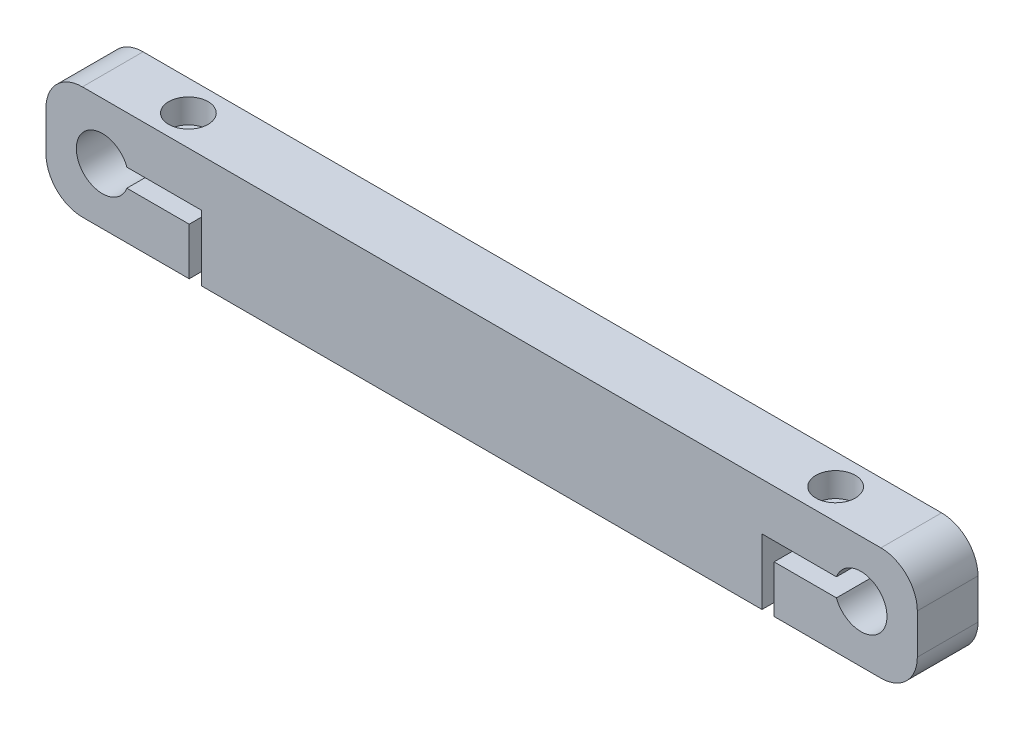
SolidWorks part; units mm, degrees
ref_plane "Alzado" through (0, 0, 0) normal (0, 0, 1) x (1, 0, 0)
ref_plane "Planta" through (0, 0, 0) normal (0, 1, 0) x (1, 0, 0)
ref_plane "Vista lateral" through (0, 0, 0) normal (1, 0, 0) x (0, 0, -1)
sketch "Croquis1" plane through (0, 0, 0) normal (0, 0, 1) x (1, 0, 0)
  line L0 (-62.5, 0) -> (62.5, 0) construction
  line L1 (-65.8, 9.3) -> (65.8, 9.3)
  line L2 (-71.8, 3.3) -> (-71.8, -3.3)
  line L3 (-65.8, -9.3) -> (65.8, -9.3)
  line L4 (71.8, 3.3) -> (71.8, -3.3)
  line L5 (-71.8, 9.3) -> (71.8, -9.3) construction
  line L6 (-71.8, -9.3) -> (71.8, 9.3) construction
  line L7 (-59.5641, 1.5) -> (-46.2, 1.5)
  line L8 (-46.2, 1.5) -> (-46.2, -9.3)
  line L9 (48.2, -1.5) -> (48.2, -9.3)
  line L10 (0, 9.3) -> (0, -9.3) construction
  line L11 (-60.6533, -1.5) -> (-48.2, -1.5)
  line L12 (-48.2, -1.5) -> (-48.2, -9.3)
  line L13 (46.2, 1.5) -> (46.2, -9.3)
  line L14 (60.6533, -1.5) -> (48.2, -1.5)
  line L15 (59.5641, 1.5) -> (46.2, 1.5)
  circle A0 centre (-62.5, 0) radius 4.3
  circle A1 centre (62.5, 0) radius 4.3
  arc A2 (65.8, 9.3) -> (71.8, 3.3) centre (65.8, 3.3) cw
  arc A3 (71.8, -3.3) -> (65.8, -9.3) centre (65.8, -3.3) cw
  arc A4 (-71.8, -3.3) -> (-65.8, -9.3) centre (-65.8, -3.3) ccw
  arc A5 (-65.8, 9.3) -> (-71.8, 3.3) centre (-65.8, 3.3) ccw
  point P0 (0, 0)
  dimension "D3" = 8.6
  dimension "D4" = 8.6
  dimension "D7" = 6
  dimension "D8" = 1.5
  dimension "D1" = 125
  dimension "D2" = 62.5
  dimension "D5" = 143.6
  dimension "D6" = 18.6
  dimension "D9" = 1.5
  dimension "D10" = 9.3
  dimension "D11" = 16.3
  dimension "D12" = 2
extrude "Saliente-Extruir1" add sketch "Croquis1" along normal blind 10
sketch "Croquis2" plane through (0, 1.5, 0) normal (0, -1, 0) x (1, 0, 0)
  line L1 (0, 10) -> (0, 0) construction
  line L3 (-58.4701, 10) -> (-58.4701, 0) construction
  line L4 (-48.2, 10) -> (-48.2, 0) construction
  circle A0 centre (-53.3351, 5) radius 1.9
  circle A1 centre (53.3351, 5) radius 1.9
  dimension "D2" = 3.8
  dimension "D1" = 5.135
  dimension "D3" = 5.1351
extrude "Cortar-Extruir1" cut sketch "Croquis2" against normal mid plane 50
sketch "Croquis5" plane through (0, 9.3, 0) normal (0, 1, 0) x (1, 0, 0)
  circle A0 centre (-53.3351, -5) radius 3.25
  circle A1 centre (53.3351, -5) radius 3.25
extrude "Cortar-Extruir3" cut sketch "Croquis5" against normal blind 4
sketch "Croquis6" plane through (0, -9.3, 0) normal (0, -1, 0) x (-1, 0, 0)
  line L1 (49.871, -5) -> (51.6031, -8)
  line L2 (51.6031, -8) -> (55.0672, -8)
  line L3 (55.0672, -8) -> (56.7992, -5)
  line L4 (56.7992, -5) -> (55.0672, -2)
  line L5 (55.0672, -2) -> (51.6031, -2)
  line L6 (51.6031, -2) -> (49.871, -5)
  line L7 (-49.871, -5) -> (-51.6031, -2)
  line L8 (-51.6031, -2) -> (-55.0672, -2)
  line L9 (-55.0672, -2) -> (-56.7992, -5)
  line L10 (-56.7992, -5) -> (-55.0672, -8)
  line L11 (-55.0672, -8) -> (-51.6031, -8)
  line L12 (-51.6031, -8) -> (-49.871, -5)
  circle A0 centre (53.3351, -5) radius 3 construction
  circle A1 centre (-53.3351, -5) radius 3 construction
  dimension "D1" = 6
  dimension "D2" = 6
extrude "Cortar-Extruir4" cut sketch "Croquis6" against normal blind 4.25
